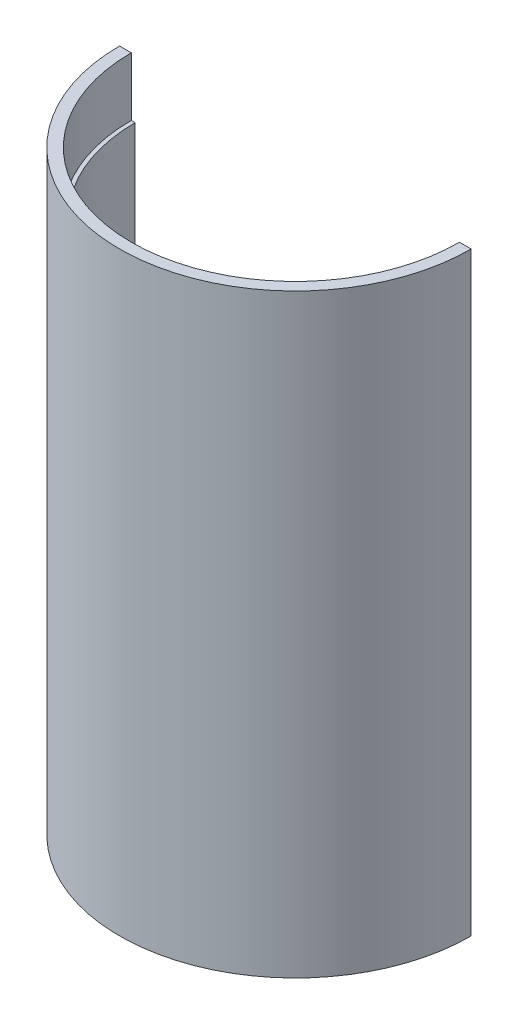
SolidWorks part; units mm, degrees
material "6061-T6 (SS)"
ref_plane "Front Plane" through (0, 0, 0) normal (0, 0, 1) x (1, 0, 0)
ref_plane "Top Plane" through (0, 0, 0) normal (0, 1, 0) x (1, 0, 0)
ref_plane "Right Plane" through (0, 0, 0) normal (1, 0, 0) x (0, 0, -1)
sketch "Sketch1" plane through (0, 0, 0) normal (0, 0, 1) x (1, 0, 0)
  line L0 (0, 0) -> (0, 68.3819) construction
  line L1 (0, 0) -> (-45, 0) construction
  line L2 (-45, 0) -> (-45, 152.3)
  line L3 (-45, 152.3) -> (-42, 152.3)
  line L4 (-42, 152.3) -> (-42, 137.3)
  line L5 (-42, 137.3) -> (-41, 137.3)
  line L6 (-41, 137.3) -> (-41, 15)
  line L7 (-41, 15) -> (-43, 15)
  line L8 (-43, 15) -> (-43, 0)
  line L9 (-43, 0) -> (-45, 0)
  dimension "D1" = 43
  dimension "D2" = 15
  dimension "D3" = 137.3
  dimension "D4" = 41
  dimension "D5" = 45
  dimension "D6" = 1
revolve "Revolve1" add sketch "Sketch1" angle 180 about L0
sketch "Sketch2" plane through (0, 0, 0) normal (1, 0, 0) x (0, 0, -1)
  line L0 (0, 0) -> (0, 6) construction
  line L1 (0, 152.3) -> (0, 0) construction
  line L2 (0, 6) -> (0, 40.3) construction
  line L3 (0, 40.3) -> (0, 91.5) construction
  circle A0 centre (0, 40.3) radius 10.45
  circle A1 centre (0, 91.5) radius 10.45
  dimension "D4" = 20.9
  dimension "D1" = 6
  dimension "D2" = 34.3
  dimension "D3" = 51.2
extrude "Cut-Extrude1" cut sketch "Sketch2" against normal through all
